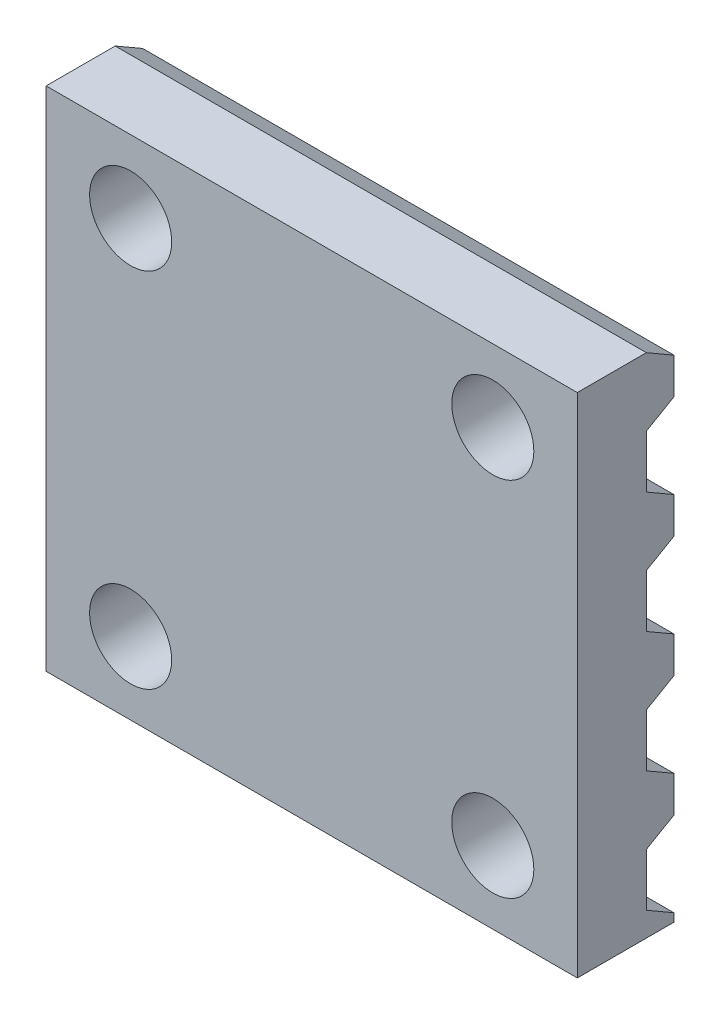
SolidWorks part; units mm, degrees
ref_plane "前视基准面" through (0, 0, 0) normal (0, 0, 1) x (1, 0, 0)
ref_plane "上视基准面" through (0, 0, 0) normal (0, 1, 0) x (1, 0, 0)
ref_plane "右视基准面" through (0, 0, 0) normal (1, 0, 0) x (0, 0, -1)
other "Configuration Table"
sketch "草图1" plane through (0, 0, 0) normal (0, 0, 1) x (1, 0, 0)
  line L0 (0, 20.0529) -> (0, -15.2305) construction
  line L1 (-11, -10.5) -> (11, -10.5)
  line L2 (-11, -10.5) -> (-11, 10.5)
  line L3 (-11, 10.5) -> (11, 10.5)
  line L4 (11, -10.5) -> (11, 10.5)
  line L5 (-11, -10.5) -> (11, 10.5) construction
  line L6 (-11, 10.5) -> (11, -10.5) construction
  line L7 (-20.5614, 0) -> (17.1896, 0) construction
  point P0 (0, 0)
  point P12 (0, 0)
  dimension "D1" = 21
  dimension "D2" = 22
extrude "凸台-拉伸1" add sketch "草图1" along normal blind 2.86
sketch "草图2" plane through (11, 0, 0) normal (1, 0, 0) x (0, 0, -1)
  line L0 (0, 10.5) -> (1.14, 9.8418)
  line L1 (1.14, 9.8418) -> (1.14, 8.3418)
  line L2 (1.14, 8.3418) -> (0, 7.6836)
  line L3 (0, -10.5) -> (0, 10.5) construction
  line L4 (0, 5.5) -> (1.14, 4.8418)
  line L5 (1.14, 4.8418) -> (1.14, 3.3418)
  line L6 (1.14, 3.3418) -> (0, 2.6836)
  line L7 (0, 0.5) -> (1.14, -0.1582)
  line L8 (1.14, -0.1582) -> (1.14, -1.6582)
  line L9 (1.14, -1.6582) -> (0, -2.3164)
  line L10 (0, -4.5) -> (1.14, -5.1582)
  line L11 (1.14, -5.1582) -> (1.14, -6.6582)
  line L12 (1.14, -6.6582) -> (0, -7.3164)
  line L13 (0, -9.5) -> (1.14, -10.1582)
  line L14 (1.14, -10.1582) -> (1.14, -10.5)
  line L15 (0, -7.3164) -> (0, -4.5)
  line L16 (0, -10.5) -> (1.14, -10.5)
  line L17 (0, -2.3164) -> (0, 0.5)
  line L18 (1.14, -11.6582) -> (0, -12.3164) [skipped]
  line L19 (0, 10.5) -> (0, 7.6836)
  line L20 (0, 5.5) -> (0, 2.6836)
  line M1 (0, -10.5) -> (0, 10.5)
  dimension "D1" = 1.14
  dimension "D2" = 1.5
  dimension "D3" = 60
  dimension "D4" = 120
  dimension "D5" = 5
extrude "凸台-拉伸2" add sketch "草图2" against normal up to surface (22 mm away) contours L16 L14 L13 M1 | L12 L11 L10 M1 | L9 L8 L7 M1 | L6 L5 L4 M1 | L2 L1 L0 M1 up to face at (-11, 0, 1.43)
sketch "草图3" plane through (0, 0, 2.86) normal (0, 0, 1) x (1, 0, 0)
  line L0 (0, 12.175) -> (0, -11.0912) construction
  line L1 (-13.9868, 0) -> (15.8495, 0) construction
  line L3 (-7.5, -7.5) -> (7.5, -7.5) construction
  line L4 (-7.5, -7.5) -> (-7.5, 7.5) construction
  line L5 (-7.5, 7.5) -> (7.5, 7.5) construction
  line L6 (7.5, -7.5) -> (7.5, 7.5) construction
  line L7 (-7.5, -7.5) -> (7.5, 7.5) construction
  line L8 (-7.5, 7.5) -> (7.5, -7.5) construction
  circle A0 centre (7.5, 7.5) radius 1.7
  circle A1 centre (7.5, -7.5) radius 1.7
  circle A2 centre (-7.5, -7.5) radius 1.7
  circle A3 centre (-7.5, 7.5) radius 1.7
  point P5 (0, 0)
  dimension "D3" = 3.4
  dimension "D4" = 3.4
  dimension "D5" = 3.4
  dimension "D6" = 3.4
  dimension "D1" = 15
  dimension "D2" = 15
extrude "切除-拉伸1" cut sketch "草图3" against normal through all both and the other way through all
